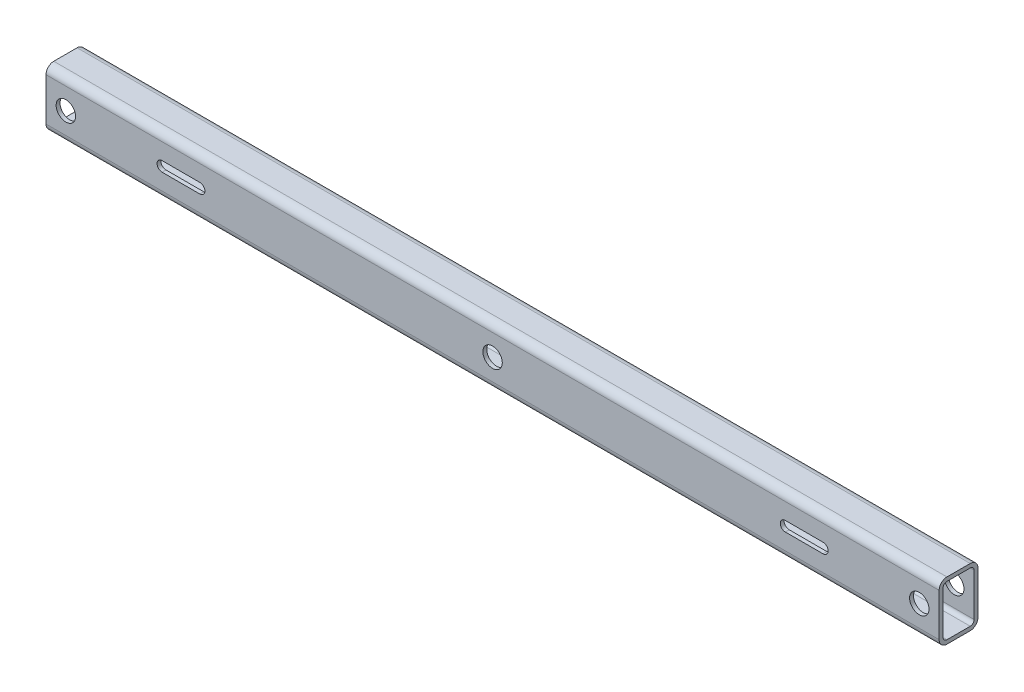
SolidWorks part; units mm, degrees
ref_plane "Front Plane" through (0, 0, 0) normal (0, 0, 1) x (1, 0, 0)
ref_plane "Top Plane" through (0, 0, 0) normal (0, 1, 0) x (1, 0, 0)
ref_plane "Right Plane" through (0, 0, 0) normal (1, 0, 0) x (0, 0, -1)
sketch "Sketch1" plane through (0, 0, 0) normal (0, 0, 1) x (1, 0, 0)
  line L1 (1150, 75) -> (-1150, 75)
  line L2 (1150, 75) -> (1150, -75)
  line L3 (1150, -75) -> (-1150, -75)
  line L4 (-1150, 75) -> (-1150, -75)
  line L5 (1150, 75) -> (-1150, -75) construction
  line L6 (1150, -75) -> (-1150, 75) construction
  point P0 (0, 0)
  dimension "D1" = 150
  dimension "D2" = 2300
extrude "Boss-Extrude1" add sketch "Sketch1" along normal blind 100
sketch "Sketch3" plane through (-1150, 0, 0) normal (-1, 0, 0) x (0, 0, 1)
  line L14 (90, -65) -> (90, 65)
  line L15 (10, -65) -> (90, -65)
  line L16 (10, 65) -> (10, -65)
  line L17 (90, 65) -> (10, 65)
  line L18 (90, -65) -> (90, 65)
  line L19 (10, -65) -> (90, -65)
  line L20 (10, 65) -> (10, -65)
  line L21 (90, 65) -> (10, 65)
  dimension "D1" = 10
extrude "Cut-Extrude1" cut sketch "Sketch3" against normal through all and the other way through all
fillet "Fillet1" radius 10 4 edges at (0, 65, 10) (0, -65, 10) (0, 65, 90) (0, -65, 90)
fillet "Fillet2" radius 20 4 edges at (0, 75, 100) (0, -75, 100) (0, -75, 0) (0, 75, 0)
sketch "Sketch4" plane through (0, 0, 0) normal (0, 0, -1) x (-1, 0, 0)
  circle A0 centre (0, 0) radius 25
  circle A1 centre (-1098.86, 0) radius 25
  circle A2 centre (1098.86, 0) radius 25
  point P7 (0, 0)
  point P8 (0, 0)
  dimension "D1" = 50
  dimension "D2" = 1098.86
  dimension "D3" = 1098.86
extrude "Cut-Extrude2" cut sketch "Sketch4" against normal through all
sketch "Sketch5" plane through (0, 0, 0) normal (0, 0, -1) x (-1, 0, 0)
  line L0 (-851.045, 0) -> (-753.695, 0) construction
  line L1 (-851.045, 12.91) -> (-753.695, 12.91)
  line L2 (-851.045, -12.91) -> (-753.695, -12.91)
  line L3 (-1150, -55) -> (-1150, 55) construction
  line L4 (0, -260.3159) -> (0, 260.3159) construction
  line L5 (851.045, 0) -> (753.695, 0) construction
  line L6 (851.045, 12.91) -> (753.695, 12.91)
  line L7 (851.045, -12.91) -> (753.695, -12.91)
  arc A0 (-851.045, 12.91) -> (-851.045, -12.91) centre (-851.045, 0) ccw
  arc A1 (-753.695, -12.91) -> (-753.695, 12.91) centre (-753.695, 0) ccw
  arc A2 (851.045, 12.91) -> (851.045, -12.91) centre (851.045, 0) cw
  arc A3 (753.695, -12.91) -> (753.695, 12.91) centre (753.695, 0) cw
  point P3 (-802.37, 0)
  point P13 (0, 0)
  point P15 (802.37, 0)
  dimension "D3" = 12.91
  dimension "D1" = 97.35
  dimension "D2" = 347.63
extrude "Cut-Extrude3" cut sketch "Sketch5" against normal through all
